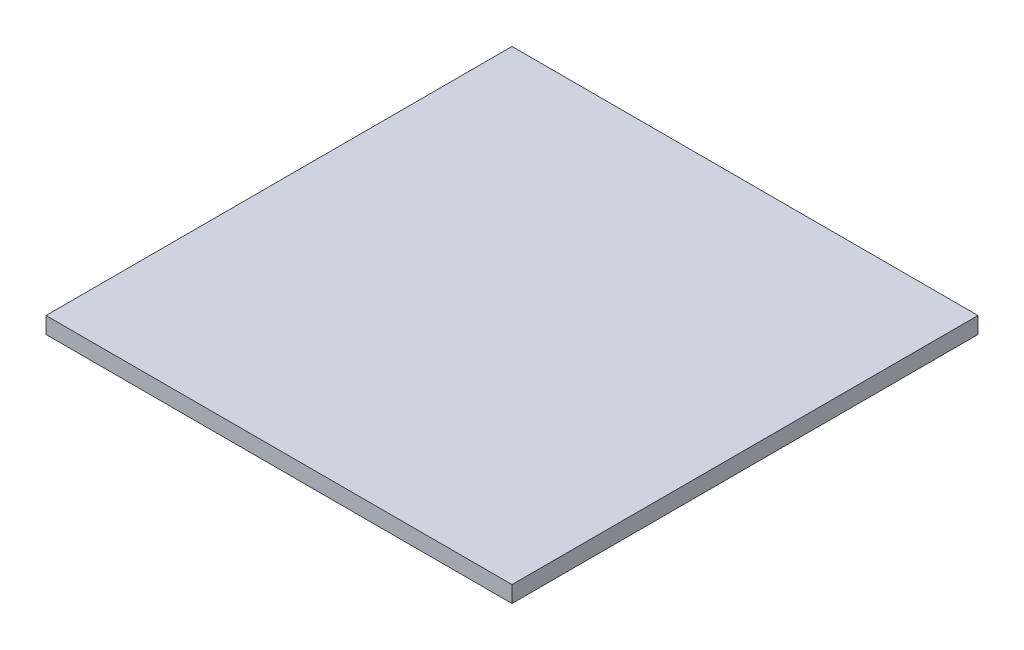
SolidWorks part; units mm, degrees
ref_plane "Front Plane" through (0, 0, 0) normal (0, 0, 1) x (1, 0, 0)
ref_plane "Top Plane" through (0, 0, 0) normal (0, 1, 0) x (1, 0, 0)
ref_plane "Right Plane" through (0, 0, 0) normal (1, 0, 0) x (0, 0, -1)
sketch "Sketch1" plane through (0, 0, 0) normal (0, 1, 0) x (1, 0, 0)
  line L1 (0, 0) -> (170, 0)
  line L2 (0, 0) -> (0, 170)
  line L3 (0, 170) -> (170, 170)
  line L4 (170, 0) -> (170, 170)
  dimension "D1" = 170
extrude "Boss-Extrude3" add sketch "Sketch1" along normal blind 6
sketch "Sketch2" plane through (0, 6, 0) normal (0, 1, 0) x (1, 0, 0)
  line L0 (0.802, 170.7945) -> (166.3179, 2.1099) construction
  line L1 (0, 3.1935) -> (170, 170)
